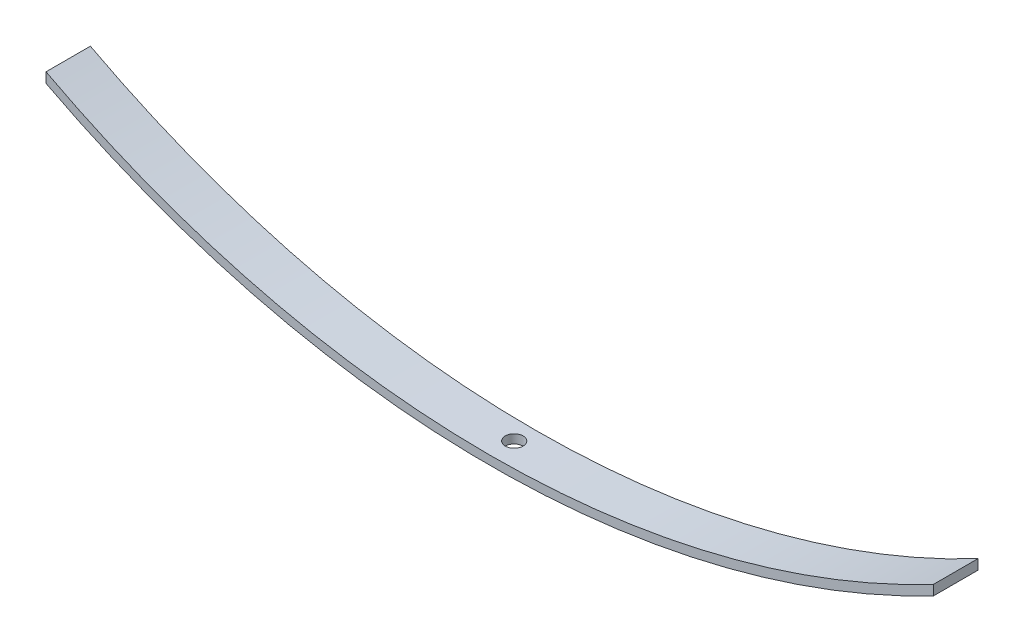
SolidWorks part; units mm, degrees
ref_plane "Front Plane" through (0, 0, 0) normal (0, 0, 1) x (1, 0, 0)
ref_plane "Top Plane" through (0, 0, 0) normal (0, 1, 0) x (1, 0, 0)
ref_plane "Right Plane" through (0, 0, 0) normal (1, 0, 0) x (0, 0, -1)
sketch "Sketch1" plane through (0, 0, 0) normal (0, 0, 1) x (1, 0, 0)
  line L0 (-500, -957.2878) -> (-500, -945.9915)
  line L1 (0, 0) -> (0, -3000.7365)
  line L2 (500, -957.2878) -> (500, -945.9915)
  arc A0 (-500, -957.2878) -> (500, -957.2878) centre (0, 0) ccw
  arc A1 (-500, -945.9915) -> (500, -945.9915) centre (0, 0) ccw
  point P7 (-500, -951.6397)
  dimension "D1" = 2160
  dimension "D2" = 2140
  dimension "D3" = 500
extrude "Boss-Extrude1" add sketch "Sketch1" along normal blind 50 contours A0 L2 A1 L0
sketch "Sketch3" plane through (0, 0, 0) normal (0, 1, 0) x (1, 0, 0)
  line L0 (0, 0) -> (0, -53.543) construction
  line L1 (500, 0) -> (-500, 0) construction
  circle A0 centre (0, -22.5) radius 10
  dimension "D1" = 20
  dimension "D2" = 22.5
extrude "Cut-Extrude1" cut sketch "Sketch3" against normal through all
